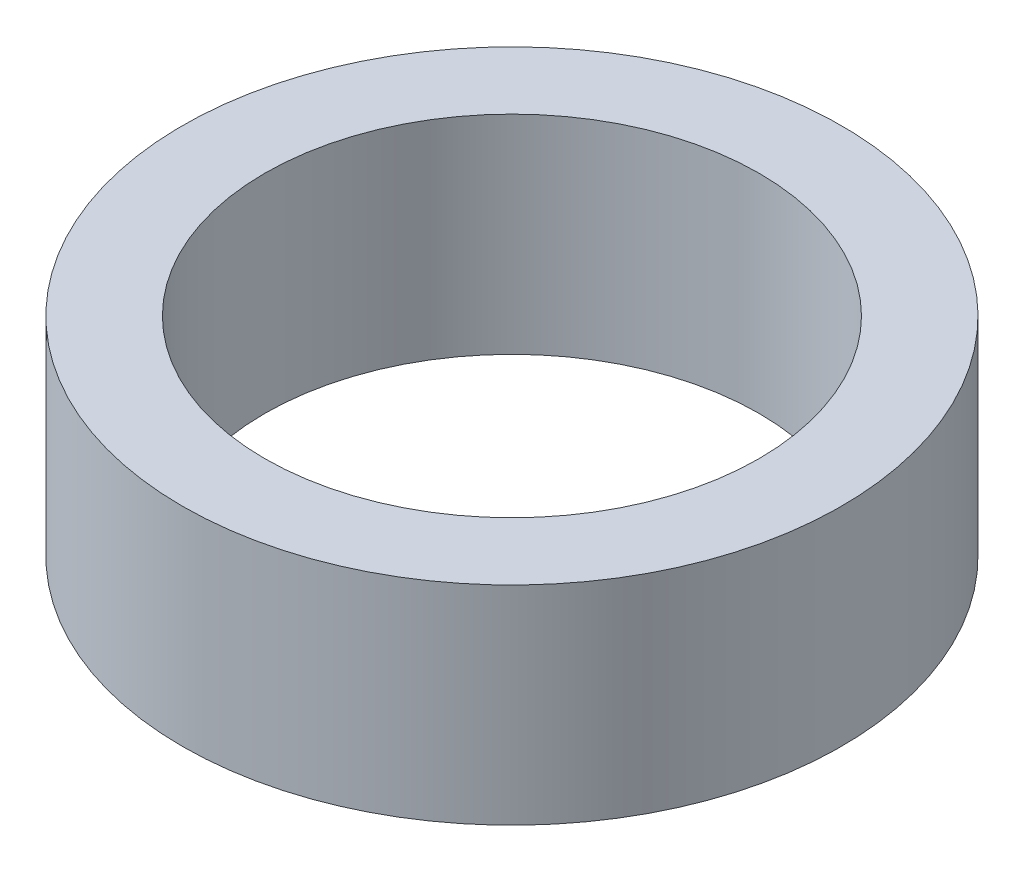
SolidWorks part; units mm, degrees
ref_plane "Front Plane" through (0, 0, 0) normal (0, 0, 1) x (1, 0, 0)
ref_plane "Top Plane" through (0, 0, 0) normal (0, 1, 0) x (1, 0, 0)
ref_plane "Right Plane" through (0, 0, 0) normal (1, 0, 0) x (0, 0, -1)
sketch "Sketch1" plane through (0, 0, 0) normal (0, 1, 0) x (1, 0, 0)
  circle A0 centre (0, 0) radius 7.62
  circle A1 centre (0, 0) radius 10.16
  dimension "D1" = 15.24
  dimension "D2" = 2.54
extrude "Boss-Extrude1" add sketch "Sketch1" along normal blind 6.4135
